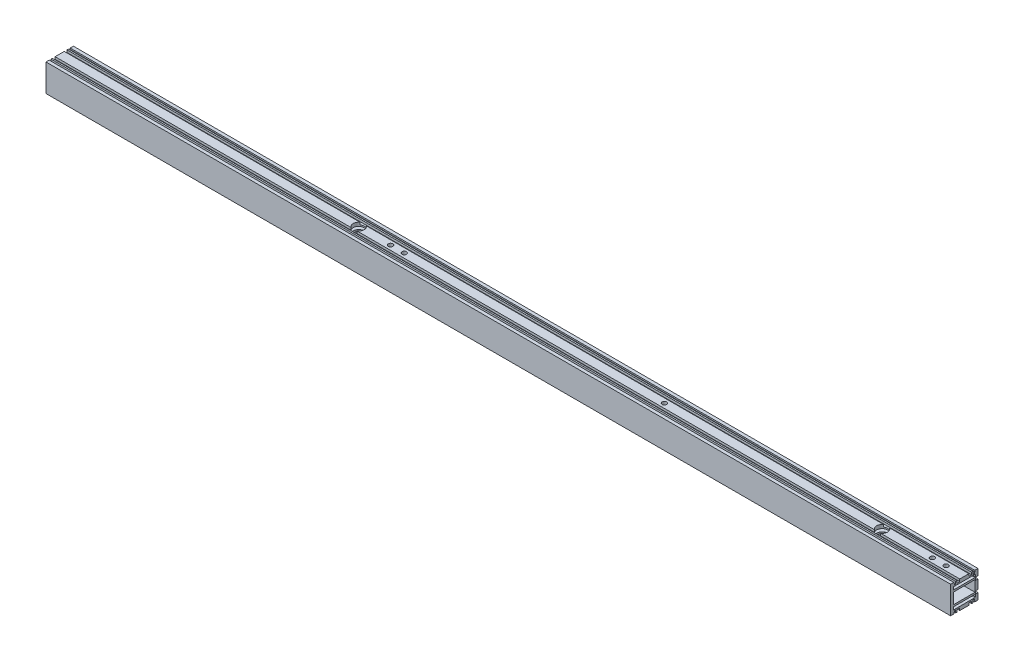
SolidWorks part; units mm, degrees
ref_plane "前视基准面" through (0, 0, 0) normal (0, 0, 1) x (1, 0, 0)
ref_plane "上视基准面" through (0, 0, 0) normal (0, 1, 0) x (1, 0, 0)
ref_plane "右视基准面" through (0, 0, 0) normal (1, 0, 0) x (0, 0, -1)
sketch "草图1" plane through (0, 0, 0) normal (1, 0, 0) x (0, 0, -1)
  line L0 (-15, 15) -> (15, -15) construction
  line L1 (-15, 15) -> (-11.5, 15)
  line L2 (-15, 15) -> (-15, -15)
  line L3 (-15, -15) -> (-11.5, -15)
  line L4 (15, 15) -> (15, 8)
  line L5 (15, 15) -> (-15, -15) construction
  line L6 (-11.5, 15) -> (-11.5, 13.5)
  line L7 (-11.5, 13.5) -> (-11, 13.5)
  line L8 (-11, 13.5) -> (-11, 12)
  line L9 (-11, 12) -> (-9.5, 12)
  line L10 (-9.5, 12) -> (-9.5, 15)
  line L11 (-9.5, 15) -> (-8, 15)
  line L12 (-8, 15) -> (-8, 12.5)
  line L13 (-8, 12.5) -> (-5, 12.5)
  line L14 (-5, 12.5) -> (-5, 15)
  line L15 (-5, 15) -> (5, 15)
  line L16 (0, 21.5201) -> (0, -18.309) construction
  line L17 (0, 55) -> (0, -55) construction
  line L18 (5, 12.5) -> (5, 15)
  line L19 (8, 12.5) -> (5, 12.5)
  line L20 (8, 15) -> (8, 12.5)
  line L21 (9.5, 15) -> (8, 15)
  line L22 (9.5, 12) -> (9.5, 15)
  line L23 (11, 12) -> (9.5, 12)
  line L24 (11, 13.5) -> (11, 12)
  line L25 (11.5, 13.5) -> (11, 13.5)
  line L26 (11.5, 15) -> (11.5, 13.5)
  line L27 (8, 15) -> (9.5, 15)
  line L28 (11.5, 15) -> (15, 15)
  line L29 (-19.8303, 0) -> (22.13, 0) construction
  line L30 (55, 0) -> (-55, 0) construction
  line L31 (8, -15) -> (9.5, -15)
  line L32 (11.5, -15) -> (11.5, -13.5)
  line L33 (11.5, -13.5) -> (11, -13.5)
  line L34 (11, -13.5) -> (11, -12)
  line L35 (11, -12) -> (9.5, -12)
  line L36 (9.5, -12) -> (9.5, -15)
  line L37 (9.5, -15) -> (8, -15)
  line L38 (8, -15) -> (8, -12.5)
  line L39 (8, -12.5) -> (5, -12.5)
  line L40 (5, -12.5) -> (5, -15)
  line L41 (-5, -15) -> (5, -15)
  line L42 (-5, -12.5) -> (-5, -15)
  line L43 (-8, -12.5) -> (-5, -12.5)
  line L44 (-8, -15) -> (-8, -12.5)
  line L45 (-9.5, -15) -> (-8, -15)
  line L46 (-9.5, -12) -> (-9.5, -15)
  line L47 (-11, -12) -> (-9.5, -12)
  line L48 (-11, -13.5) -> (-11, -12)
  line L49 (-11.5, -13.5) -> (-11, -13.5)
  line L50 (-11.5, -15) -> (-11.5, -13.5)
  line L51 (-9.5, -15) -> (-8, -15)
  line L52 (-5, -15) -> (5, -15)
  line L53 (8, -15) -> (9.5, -15)
  line L54 (11.5, -15) -> (15, -15)
  line L55 (15, 8) -> (12.5, 8)
  line L56 (12.5, 8) -> (12.5, 5)
  line L57 (12.5, 5) -> (15, 5)
  line L58 (12.5, -5) -> (15, -5)
  line L59 (12.5, -8) -> (12.5, -5)
  line L60 (15, -8) -> (12.5, -8)
  line L61 (15, 5) -> (15, -5)
  line L62 (15, -8) -> (15, -15)
  line L63 (12, -10.5) -> (12, -8.5)
  line L64 (-11.5, 11) -> (11.5, 11)
  line L65 (-12, 10.5) -> (-12, 8.5)
  line L66 (-11.5, 8) -> (11.5, 8)
  line L67 (12, 10.5) -> (12, 8.5)
  line L68 (-11.5, -8) -> (11.5, -8)
  line L69 (-12, -10.5) -> (-12, -8.5)
  line L70 (-11.5, -11) -> (11.5, -11)
  line L72 (-11.75, 6) -> (11.75, 6)
  line L73 (-11.75, 6) -> (-11.75, -6)
  line L74 (-11.75, -6) -> (11.75, -6)
  line L75 (11.75, 6) -> (11.75, -6)
  arc A0 (12, 8.5) -> (11.5, 8) centre (11.5, 8.5) cw
  arc A1 (11.5, 11) -> (12, 10.5) centre (11.5, 10.5) cw
  arc A2 (-11.5, 11) -> (-12, 10.5) centre (-11.5, 10.5) ccw
  arc A3 (-11.5, 8) -> (-12, 8.5) centre (-11.5, 8.5) cw
  arc A8 (-11.5, -8) -> (-12, -8.5) centre (-11.5, -8.5) ccw
  arc A9 (-11.5, -11) -> (-12, -10.5) centre (-11.5, -10.5) cw
  arc A10 (11.5, -11) -> (12, -10.5) centre (11.5, -10.5) ccw
  arc A11 (12, -8.5) -> (11.5, -8) centre (11.5, -8.5) ccw
  point P69 (12, 11)
  point P72 (-12, 11)
  point P77 (-11, -13.5)
  point P80 (11, -13.5)
  point P83 (11, 13.5)
  point P86 (-11, 13.5)
  point P99 (-12, -11)
  point P100 (12, -11)
  dimension "D17" = 0.5
  dimension "D1" = 3.5
  dimension "D2" = 1.5
  dimension "D3" = 0.5
  dimension "D4" = 1.5
  dimension "D5" = 3
  dimension "D6" = 30
  dimension "D7" = 30
  dimension "D8" = 1.5
  dimension "D9" = 2.5
  dimension "D10" = 3
  dimension "D11" = 2.5
  dimension "D12" = 7
  dimension "D13" = 3
  dimension "D14" = 4
  dimension "D15" = 3
  dimension "D16" = 24
  dimension "D19" = 23.5
  dimension "D20" = 12
extrude "凸台-拉伸1" add sketch "草图1" along normal mid plane 991
hole_wizard "M6 螺纹孔1" positions "草图3" profile "草图2" tap size "M6" standard "GB"
sketch "草图3" plane through (0, 0, -15) normal (0, 0, -1) x (-1, 0, 0)
  line L0 (-495.5, -15) -> (495.5, -15) construction
  line L1 (495.5, 5) -> (495.5, -5) construction
  point P2 (445.5, 0)
  point P5 (430.5, 0)
  point P8 (370.5, 0)
  point P10 (266.5, 0)
  point P17 (394.5, 0)
  dimension "D1" = 15
  dimension "D2" = 15
  dimension "D3" = 104
  dimension "D4" = 125
  dimension "D5" = 15
  dimension "D6" = 101
sketch "草图2" plane through (-445.5, 0, -15) normal (1, 0, 0) x (0, 1, 0)
  line L0 (0, 0) -> (0, 20.5022)
  line L1 (0, 20.5022) -> (2.5, 19)
  line L2 (2.5, 19) -> (2.5, 0)
  line L5 (2.5, 0) -> (0, 0)
  line L10 (0, 20.5022) -> (-2.5, 19) construction
  line L11 (0, -6.35) -> (0, 107.95) construction
  dimension "螺纹孔钻头直径" = 5
  dimension "螺纹孔钻头深度" = 19
  dimension "导头角度" = 118
cosmetic thread "孔螺蚊线1" parameters "D1"=3.25, "D2"=6
cosmetic thread "孔螺蚊线2" parameters "D1"=3.25, "D2"=6
cosmetic thread "孔螺蚊线13" parameters "D1"=3.25, "D2"=6
cosmetic thread "孔螺蚊线14" parameters "D1"=3.25, "D2"=6
cosmetic thread "孔螺蚊线22" parameters "D1"=3.25, "D2"=6
hole_wizard "M6 螺纹孔2" positions "草图5" profile "草图4" tap size "M6" standard "GB"
sketch "草图5" plane through (0, 15, 0) normal (0, 1, 0) x (1, 0, 0)
  line L0 (495.5, 15) -> (-495.5, 15) construction
  line L1 (-495.5, -5) -> (-495.5, 5) construction
  point P0 (-133, 0)
  point P3 (-118, 0)
  point P6 (460.5, 0)
  point P9 (475.5, 0)
  point P12 (167, 0)
  dimension "D1" = 15
  dimension "D2" = 662.5
sketch "草图4" plane through (-133, 15, 0) normal (1, 0, 0) x (0, 0, 1)
  line L0 (0, 0) -> (0, 20.5022)
  line L1 (0, 20.5022) -> (2.5, 19)
  line L2 (2.5, 19) -> (2.5, 0)
  line L5 (2.5, 0) -> (0, 0)
  line L10 (0, 20.5022) -> (-2.5, 19) construction
  line L11 (0, -6.35) -> (0, 107.95) construction
  dimension "螺纹孔钻头直径" = 5
  dimension "螺纹孔钻头深度" = 19
  dimension "导头角度" = 118
cosmetic thread "孔螺蚊线3" parameters "D1"=9, "D2"=6
cosmetic thread "孔螺蚊线4" parameters "D1"=9, "D2"=6
cosmetic thread "孔螺蚊线5" parameters "D1"=9, "D2"=6
cosmetic thread "孔螺蚊线6" parameters "D1"=9, "D2"=6
cosmetic thread "孔螺蚊线25" parameters "D1"=9, "D2"=6
hole_wizard "M6 螺纹孔3" positions "草图7" profile "草图6" tap size "M6" standard "GB"
sketch "草图7" plane through (0, -15, 0) normal (0, -1, 0) x (-1, 0, 0)
  point P0 (445.5, 0)
  point P3 (430.5, 0)
  point P6 (-230.5, 0)
  point P9 (-245.5, 0)
  point P12 (-460.5, 0)
  point P15 (-475.5, 0)
sketch "草图6" plane through (-445.5, -15, 0) normal (1, 0, 0) x (0, 0, -1)
  line L0 (0, 0) -> (0, 20.5022)
  line L1 (0, 20.5022) -> (2.5, 19)
  line L2 (2.5, 19) -> (2.5, 0)
  line L5 (2.5, 0) -> (0, 0)
  line L10 (0, 20.5022) -> (-2.5, 19) construction
  line L11 (0, -6.35) -> (0, 107.95) construction
  dimension "螺纹孔钻头直径" = 5
  dimension "螺纹孔钻头深度" = 19
  dimension "导头角度" = 118
cosmetic thread "孔螺蚊线7" parameters "D1"=9, "D2"=6
cosmetic thread "孔螺蚊线8" parameters "D1"=9, "D2"=6
cosmetic thread "孔螺蚊线9" parameters "D1"=9, "D2"=6
cosmetic thread "孔螺蚊线10" parameters "D1"=9, "D2"=6
cosmetic thread "孔螺蚊线11" parameters "D1"=9, "D2"=6
cosmetic thread "孔螺蚊线12" parameters "D1"=9, "D2"=6
hole_wizard "M4 螺纹孔1" positions "草图11" profile "草图10" tap size "M4" standard "GB"
sketch "草图11" plane through (0, 0, -15) normal (0, 0, -1) x (-1, 0, 0)
  line L0 (495.5, 5) -> (495.5, -5) construction
  line L1 (-495.5, -15) -> (495.5, -15) construction
  point P0 (191, 0)
  point P2 (236, 0)
  point P20 (341, 0)
  point P22 (296, 0)
  dimension "D1" = 259.5
  dimension "D2" = 15
  dimension "D3" = 15
  dimension "D4" = 45
  dimension "D5" = 45
  dimension "D6" = 15
  dimension "D7" = 15
  dimension "D8" = 154.5
sketch "草图10" plane through (-191, 0, -15) normal (1, 0, 0) x (0, 1, 0)
  line L0 (0, 0) -> (0, 15.9914)
  line L1 (0, 15.9914) -> (1.65, 15)
  line L2 (1.65, 15) -> (1.65, 0)
  line L5 (1.65, 0) -> (0, 0)
  line L10 (0, 15.9914) -> (-1.65, 15) construction
  line L11 (0, -6.35) -> (0, 107.95) construction
  dimension "螺纹孔钻头直径" = 3.3
  dimension "螺纹孔钻头深度" = 15
  dimension "导头角度" = 118
cosmetic thread "孔螺蚊线19" parameters "D1"=3.25, "D2"=4
cosmetic thread "孔螺蚊线20" parameters "D1"=3.25, "D2"=4
cosmetic thread "孔螺蚊线23" parameters "D1"=3.25, "D2"=4
cosmetic thread "孔螺蚊线24" parameters "D1"=3.25, "D2"=4
hole_wizard "Ø12.0 (12) 直径孔1" positions "草图13" profile "草图12" hole size "Ø12.0" standard "GB" end condition through all
sketch "草图13" plane through (0, -15, 0) normal (0, -1, 0) x (-1, 0, 0)
  line L0 (-495.5, 15) -> (495.5, 15) construction
  line L1 (-495.5, 11.5) -> (-495.5, 15) construction
  line L2 (495.5, -5) -> (495.5, 5) construction
  point P0 (168, 0)
  point P9 (-405.5, 0)
  dimension "D1" = 15
  dimension "D2" = 90
  dimension "D3" = 15
  dimension "D4" = 327.5
sketch "草图12" plane through (-168, -15, 0) normal (1, 0, 0) x (0, 0, -1)
  line L0 (0, 0) -> (0, 30)
  line L1 (0, 30) -> (6, 30)
  line L2 (6, 30) -> (6, 0)
  line L5 (6, 0) -> (0, 0)
  line L11 (0, -6.35) -> (0, 107.95) construction
  dimension "通孔孔直径" = 12
  dimension "通孔孔深度" = 30
